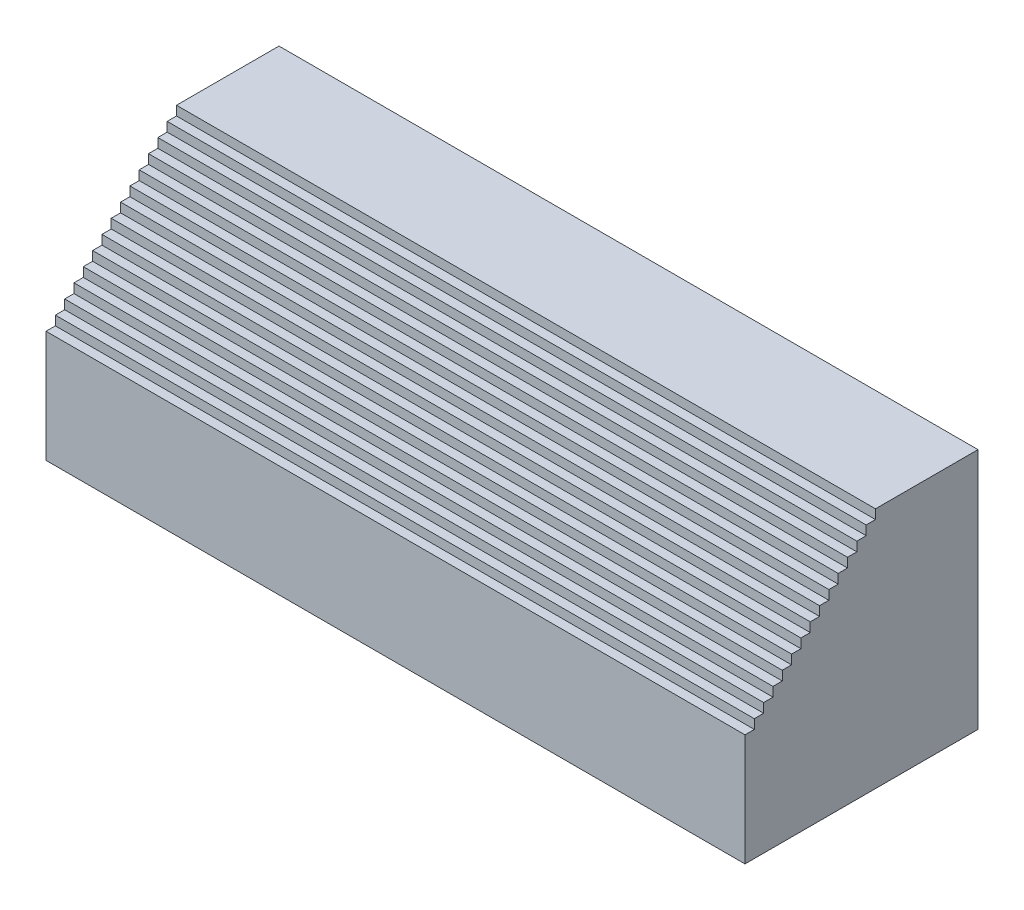
SolidWorks part; units mm, degrees
ref_plane "前视基准面" through (0, 0, 0) normal (0, 0, 1) x (1, 0, 0)
ref_plane "上视基准面" through (0, 0, 0) normal (0, 1, 0) x (1, 0, 0)
ref_plane "右视基准面" through (0, 0, 0) normal (1, 0, 0) x (0, 0, -1)
sketch "草图1" plane through (0, 0, 0) normal (0, 1, 0) x (1, 0, 0)
  line L1 (-7.5, 2.5) -> (7.5, 2.5)
  line L2 (-7.5, 2.5) -> (-7.5, -2.5)
  line L3 (-7.5, -2.5) -> (7.5, -2.5)
  line L4 (7.5, 2.5) -> (7.5, -2.5)
  dimension "D1" = 5
  dimension "D2" = 15
  dimension "D3" = 7.5
  dimension "D4" = 2.5
extrude "凸台-拉伸1" add sketch "草图1" along normal blind 5.2
sketch "草图6" plane through (7.5, 0, 0) normal (1, 0, 0) x (0, 0, -1)
  line L0 (-2.5, 2.4) -> (-2.3, 2.4)
  line L1 (-2.5, 5.2) -> (-2.5, 0) construction
  line L2 (-2.3, 2.4) -> (-2.3, 2.6)
  line L3 (-2.3, 2.6) -> (-2.1, 2.6)
  line L4 (-2.1, 2.6) -> (-2.1, 2.8)
  line L5 (-2.1, 2.8) -> (-1.9, 2.8)
  line L6 (-1.9, 2.8) -> (-1.9, 3)
  line L7 (-1.9, 3) -> (-1.7, 3)
  line L8 (-1.7, 3) -> (-1.7, 3.2)
  line L9 (-1.7, 3.2) -> (-1.5, 3.2)
  line L10 (-1.5, 3.2) -> (-1.5, 3.4)
  line L11 (-1.5, 3.4) -> (-1.3, 3.4)
  line L12 (-1.3, 3.4) -> (-1.3, 3.6)
  line L13 (-1.3, 3.6) -> (-1.1, 3.6)
  line L14 (-1.1, 3.6) -> (-1.1, 3.8)
  line L15 (-1.1, 3.8) -> (-0.9, 3.8)
  line L16 (-0.9, 3.8) -> (-0.9, 4)
  line L17 (-0.9, 4) -> (-0.7, 4)
  line L18 (-0.7, 4) -> (-0.7, 4.2)
  line L19 (-0.7, 4.2) -> (-0.5, 4.2)
  line L20 (-0.5, 4.2) -> (-0.5, 4.4)
  line L21 (-0.5, 4.4) -> (-0.3, 4.4)
  line L22 (-0.3, 4.4) -> (-0.3, 4.6)
  line L23 (-0.3, 4.6) -> (-0.1, 4.6)
  line L24 (-0.1, 4.6) -> (-0.1, 4.8)
  line L25 (-0.1, 4.8) -> (0.1003, 4.8)
  line L26 (0.1003, 4.8) -> (0.1003, 5)
  line L27 (0.1003, 5) -> (0.3003, 5)
  line L28 (0.3003, 5) -> (0.3003, 5.2)
  line L34 (-2.5, 0) -> (2.5, 0) construction
  line L36 (-2.5, 2.4) -> (-2.5, 5.2)
  line L37 (-2.5, 5.2) -> (0.3003, 5.2)
  dimension "D1" = 2.4
  dimension "D2" = 0.2
  dimension "D3" = 0.2
  dimension "D4" = 0.2
  dimension "D5" = 0.2
  dimension "D6" = 0.2
  dimension "D7" = 0.2
  dimension "D8" = 0.2
  dimension "D9" = 0.2
  dimension "D10" = 0.2
  dimension "D11" = 0.2
  dimension "D12" = 0.2
  dimension "D13" = 0.2
  dimension "D14" = 0.2003
  dimension "D15" = 0.2
  dimension "D16" = 0.2
  dimension "D17" = 0.2
  dimension "D18" = 0.2
  dimension "D19" = 0.2
  dimension "D20" = 0.2
  dimension "D21" = 0.2
  dimension "D22" = 0.2
  dimension "D23" = 0.2
  dimension "D24" = 0.2
  dimension "D25" = 0.2
  dimension "D26" = 0.2
  dimension "D27" = 0.2
  dimension "D28" = 0.2
  dimension "D29" = 0.2
other "对齐组1"
extrude "切除-拉伸1" cut sketch "草图6" against normal through all
